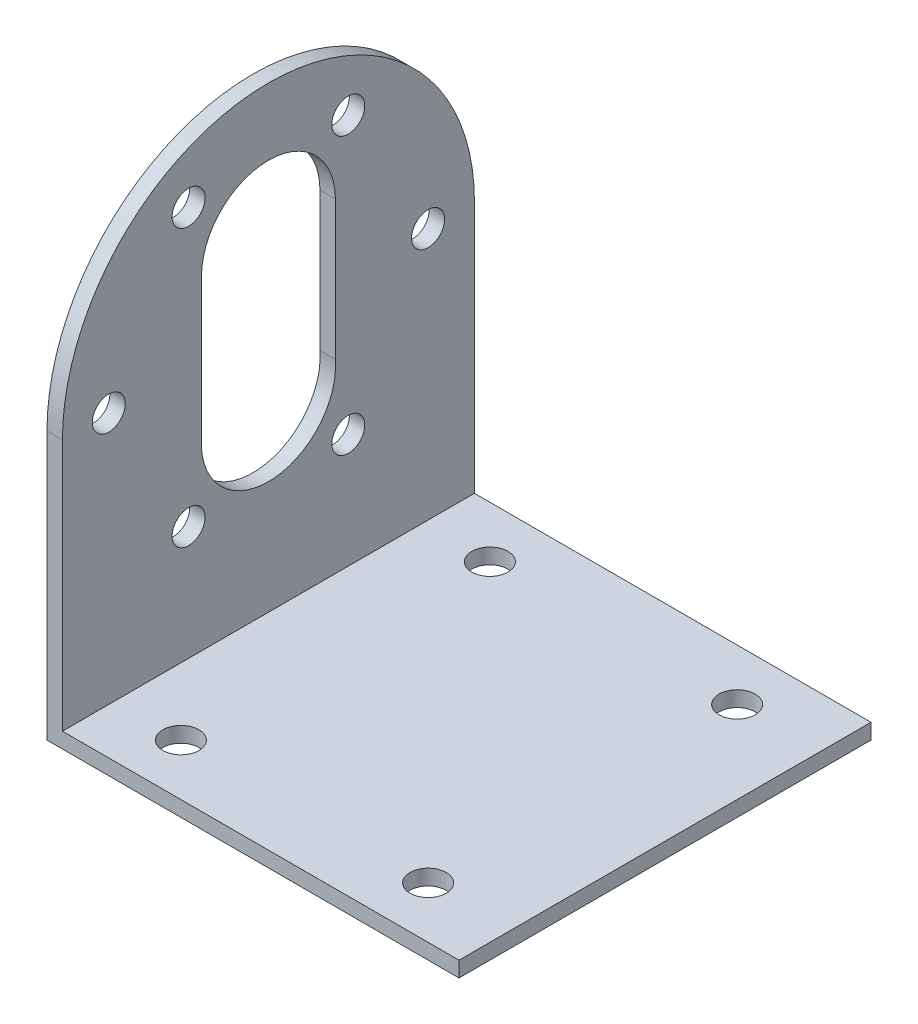
SolidWorks part; units mm, degrees
ref_plane "前视基准面" through (0, 0, 0) normal (0, 0, 1) x (1, 0, 0)
ref_plane "上视基准面" through (0, 0, 0) normal (0, 1, 0) x (1, 0, 0)
ref_plane "右视基准面" through (0, 0, 0) normal (1, 0, 0) x (0, 0, -1)
sketch "草图1" plane through (0, 0, 0) normal (0, 1, 0) x (1, 0, 0)
  line L1 (-20, 20) -> (20, 20)
  line L2 (-20, 20) -> (-20, -20)
  line L3 (-20, -20) -> (20, -20)
  line L4 (20, 20) -> (20, -20)
  line L5 (-20, 20) -> (20, -20) construction
  line L6 (-20, -20) -> (20, 20) construction
  point P0 (0, 0)
  dimension "D1" = 40
  dimension "D2" = 40
extrude "凸台-拉伸1" add sketch "草图1" along normal blind 1.5
sketch "草图4" plane through (-20, 0, 0) normal (-1, 0, 0) x (0, 0, 1)
  line L0 (0, 0) -> (0, 26) construction
  line L1 (20, 0) -> (20, 26)
  line L2 (-20, 26) -> (-20, 0)
  line L3 (-20, 0) -> (20, 0)
  line L4 (0, 26) -> (15.5, 26) construction
  line L5 (-6.5, 33) -> (-6.5, 19)
  line L6 (6.5, 33) -> (6.5, 19)
  arc A0 (20, 26) -> (-20, 26) centre (0, 26) ccw
  circle A1 centre (15.5, 26) radius 1.6
  circle A2 centre (7.75, 12.5766) radius 1.6
  circle A3 centre (-7.75, 12.5766) radius 1.6
  circle A4 centre (-15.5, 26) radius 1.6
  circle A5 centre (-7.75, 39.4234) radius 1.6
  circle A6 centre (7.75, 39.4234) radius 1.6
  arc A7 (6.5, 33) -> (-6.5, 33) centre (0, 33) ccw
  arc A8 (-6.5, 19.5289) -> (6.5, 19.5289) centre (0, 19) ccw
  point P23 (0, 26)
  line M6 (20, 1.5) -> (-20, 1.5)
  dimension "D2" = 15.5
  dimension "D3" = 3.2
  dimension "D5" = 13
  dimension "D6" = 7
  dimension "D1" = 26
  dimension "D7" = 14
  dimension "D4" = 6
extrude "凸台-拉伸2" add sketch "草图4" against normal blind 1.5 contours L1 A0 L2 A8 L5 A7 L6 A6 A5 A4 A3 A2 A1 M6
sketch "草图5" plane through (0, 1.5, 0) normal (0, 1, 0) x (1, 0, 0)
  line L0 (19.353, 0) -> (-17.7613, 0) construction
  line L1 (12, 15.6633) -> (12, -18.1231) construction
  line L2 (20, -20) -> (20, 20) construction
  line L3 (0, 4.0153) -> (0, -5.3899) construction
  circle A0 centre (12, -15) radius 1.75
  circle A1 centre (12, 15) radius 1.75
  circle A2 centre (-12, -15) radius 1.75
  circle A3 centre (-12, 15) radius 1.75
  dimension "D2" = 3.5
  dimension "D3" = 15
  dimension "D1" = 8
extrude "切除-拉伸1" cut sketch "草图5" against normal blind 1.5
